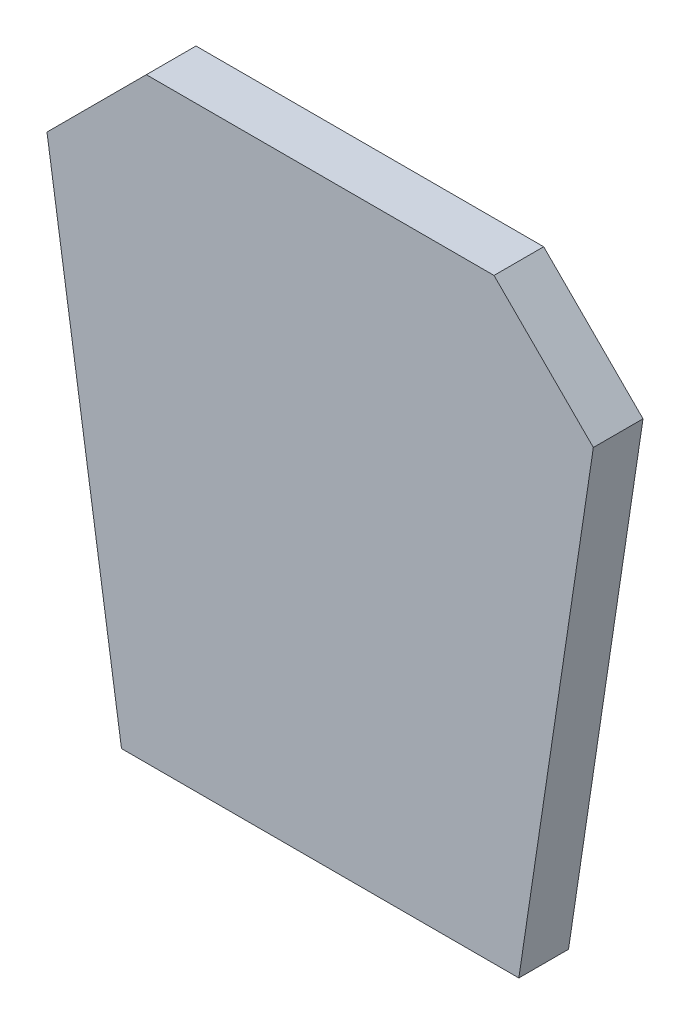
SolidWorks part; units mm, degrees
ref_plane "Front Plane" through (0, 0, 0) normal (0, 0, 1) x (1, 0, 0)
ref_plane "Top Plane" through (0, 0, 0) normal (0, 1, 0) x (1, 0, 0)
ref_plane "Right Plane" through (0, 0, 0) normal (1, 0, 0) x (0, 0, -1)
sketch "Sketch1" plane through (0, 0, 0) normal (0, 0, 1) x (1, 0, 0)
  line L0 (200, 0) -> (-200, 0)
  line L1 (0, 0) -> (0, 600) construction
  line L2 (-200, 0) -> (-275, 500)
  line L3 (-275, 500) -> (-175, 600)
  line L4 (-175, 600) -> (0, 600)
  line L5 (175, 600) -> (0, 600)
  line L6 (275, 500) -> (175, 600)
  line L7 (200, 0) -> (275, 500)
  point P3 (-275, 471.8546)
  point P7 (-100, 579.1721)
  dimension "D1" = 200
  dimension "D2" = 600
  dimension "D3" = 75
  dimension "D4" = 100
  dimension "D5" = 100
  dimension "D6" = 175
extrude "Boss-Extrude1" add sketch "Sketch1" along normal blind 50
